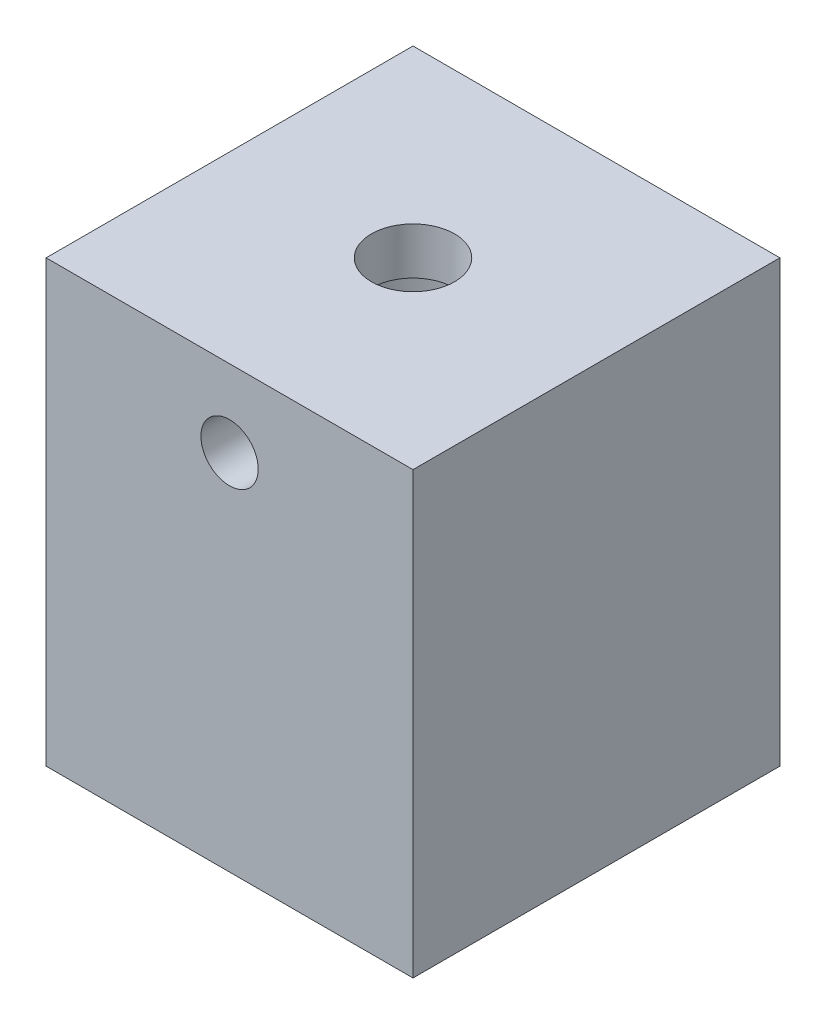
SolidWorks part; units mm, degrees
ref_plane "Front Plane" through (0, 0, 0) normal (0, 0, 1) x (1, 0, 0)
ref_plane "Top Plane" through (0, 0, 0) normal (0, 1, 0) x (1, 0, 0)
ref_plane "Right Plane" through (0, 0, 0) normal (1, 0, 0) x (0, 0, -1)
sketch "Sketch1" plane through (0, 0, 0) normal (0, 1, 0) x (1, 0, 0)
  line L1 (-25.4, -25.4) -> (25.4, -25.4)
  line L2 (-25.4, -25.4) -> (-25.4, 25.4)
  line L3 (-25.4, 25.4) -> (25.4, 25.4)
  line L4 (25.4, -25.4) -> (25.4, 25.4)
  line L5 (-25.4, -25.4) -> (25.4, 25.4) construction
  line L6 (-25.4, 25.4) -> (25.4, -25.4) construction
  point P0 (0, 0)
  dimension "D1" = 50.8
  dimension "D2" = 50.8
extrude "Block" add sketch "Sketch1" along normal blind 60.96
hole_wizard "Spring Bore" positions "Sketch3" profile "Sketch2" hole size "1" standard "ANSI Inch"
sketch "Sketch3" plane through (0, 0, 0) normal (0, -1, 0) x (-1, 0, 0)
  point P0 (0, 0)
sketch "Sketch2" plane through (0, 0, 0) normal (1, 0, 0) x (0, 0, -1)
  line L0 (0, 0) -> (0, 57.9229)
  line L1 (0, 57.9229) -> (12.7, 50.292)
  line L2 (12.7, 50.292) -> (12.7, 0)
  line L5 (12.7, 0) -> (0, 0)
  line L10 (0, 57.9229) -> (-12.7, 50.292) construction
  line L11 (0, -6.35) -> (0, 107.95) construction
  dimension "Hole Dia." = 25.4
  dimension "Hole Depth" = 50.292
  dimension "Drill Angle" = 118
hole_wizard "1/2-20 Tapped Hole" positions "Sketch5" profile "Sketch4" tap size "1/2-20" standard "ANSI Inch" end condition through all
sketch "Sketch5" plane through (0, 60.96, 0) normal (0, 1, 0) x (1, 0, 0)
  point P0 (0, 0)
sketch "Sketch4" plane through (0, 60.96, 0) normal (1, 0, 0) x (0, 0, 1)
  line L0 (0, 0) -> (0, 60.96)
  line L1 (0, 60.96) -> (5.7544, 60.96)
  line L2 (5.7544, 60.96) -> (5.7544, 0)
  line L5 (5.7544, 0) -> (0, 0)
  line L11 (0, -6.35) -> (0, 107.95) construction
  dimension "Thread Major Dia." = 11.5087
  dimension "Thru Tap Drill Depth" = 60.96
hole_wizard "#10-32 Tapped Holes" positions "Sketch7" profile "Sketch6" tap size "#10-32" standard "ANSI Inch"
sketch "Sketch7" plane through (0, 0, 0) normal (0, -1, 0) x (-1, 0, 0)
  line L1 (-11.1125, -12.7) -> (11.1125, -12.7) construction
  line L2 (-11.1125, -12.7) -> (-11.1125, 12.7) construction
  line L3 (-11.1125, 12.7) -> (11.1125, 12.7) construction
  line L4 (11.1125, -12.7) -> (11.1125, 12.7) construction
  line L5 (-11.1125, -12.7) -> (11.1125, 12.7) construction
  line L6 (-11.1125, 12.7) -> (11.1125, -12.7) construction
  point P0 (11.1125, 12.7)
  point P2 (11.1125, -12.7)
  point P4 (-11.1125, -12.7)
  point P6 (-11.1125, 12.7)
  point P83 (0, 0)
  dimension "D1" = 25.4
  dimension "S1" = 22.225
sketch "Sketch6" plane through (-11.1125, 0, -12.7) normal (1, 0, 0) x (0, 0, -1)
  line L0 (0, 0) -> (0, 20.2633)
  line L1 (0, 20.2633) -> (2.0193, 19.05)
  line L2 (2.0193, 19.05) -> (2.0193, 0)
  line L5 (2.0193, 0) -> (0, 0)
  line L10 (0, 20.2633) -> (-2.0193, 19.05) construction
  line L11 (0, -6.35) -> (0, 107.95) construction
  dimension "Tap Drill Dia." = 4.0386
  dimension "Tap Drill Depth" = 19.05
  dimension "Drill Angle" = 118
hole_wizard "View Hole" positions "Sketch10" profile "Sketch9" hole size "5/16" standard "ANSI Inch" end condition through all
sketch "Sketch10" plane through (0, 0, 25.4) normal (0, 0, 1) x (1, 0, 0)
  line L0 (12.7, 50.292) -> (-12.7, 50.292) construction
  point P0 (0, 50.292)
sketch "Sketch9" plane through (0, 50.292, 25.4) normal (1, 0, 0) x (0, -1, 0)
  line L0 (0, 0) -> (0, 50.8)
  line L1 (0, 50.8) -> (3.9687, 50.8)
  line L2 (3.9687, 50.8) -> (3.9687, 0)
  line L5 (3.9687, 0) -> (0, 0)
  line L11 (0, -6.35) -> (0, 107.95) construction
  dimension "Thru Hole Dia." = 7.9375
  dimension "Thru Hole Depth" = 50.8
